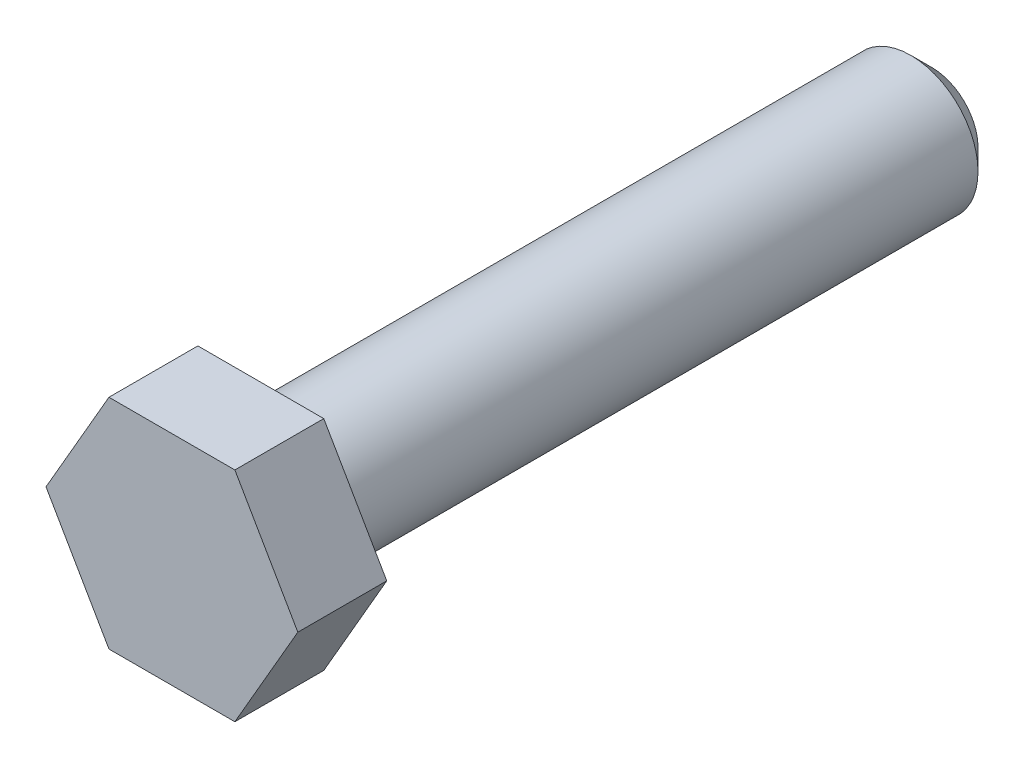
SolidWorks part; units mm, degrees
ref_plane "Plane1" through (0, 0, 0) normal (0, 0, 1) x (1, 0, 0)
ref_plane "MSC_PF1" through (0, 0, 0) normal (0, 1, 0) x (1, 0, 0)
ref_plane "Plane3" through (0, 0, 0) normal (1, 0, 0) x (0, 0, -1)
sketch "Sketch1" plane through (0, 0, 0) normal (0, 0, 1) x (1, 0, 0)
  line L0 (0, 0) -> (1, 0) construction
  line L1 (-3.7528, 6.5) -> (3.7528, 6.5)
  line L2 (-3.7528, -6.5) -> (3.7528, -6.5)
  line L3 (3.7528, 6.5) -> (7.5056, 0)
  line L4 (7.5056, 0) -> (3.7528, -6.5)
  line L5 (-3.7528, 6.5) -> (-7.5056, 0)
  line L6 (-7.5056, 0) -> (-3.7528, -6.5)
  circle A0 centre (0, 0) radius 6.5 construction
  dimension "P" = 1
  dimension "s" = 13
extrude "Base-Extrude" add sketch "Sketch1" along normal blind 5.3
sketch "Sketch3" plane through (0, 0, 0) normal (0, 0, -1) x (-1, 0, 0)
  circle A0 centre (0, 0) radius 4
  dimension "_d" = 8
extrude "Boss-Extrude1" add sketch "Sketch3" along normal blind 40
cosmetic thread "Условное изображение резьбы2" parameters "D2"=7
chamfer "Chamfer1" distance 1.25 angle 45 1 edges at (-4, 0, -40)
